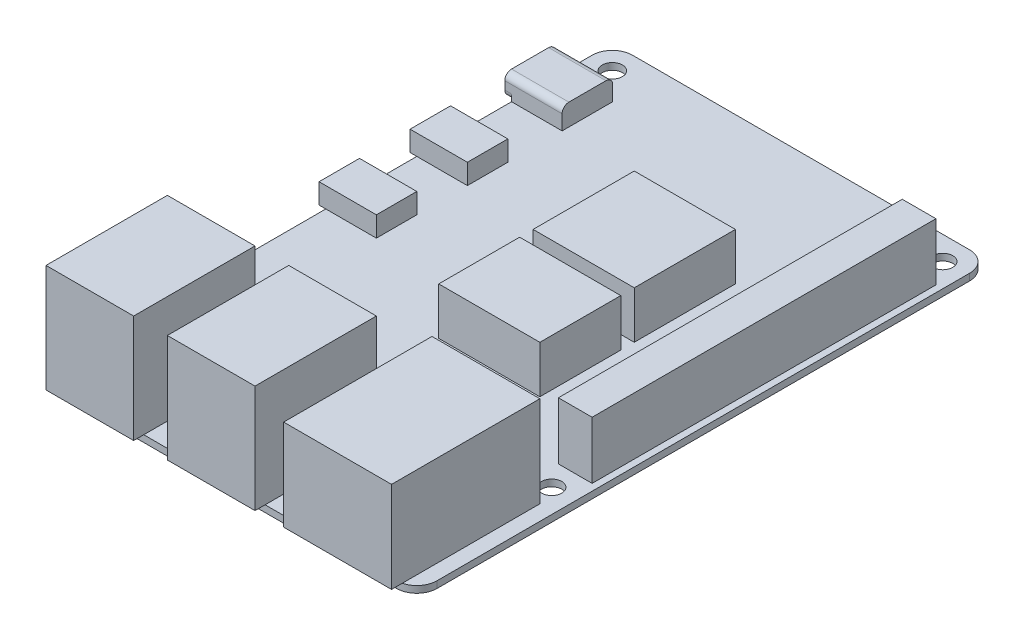
SolidWorks part; units mm, degrees
ref_plane "Plan de face" through (0, 0, 0) normal (0, 0, 1) x (1, 0, 0)
ref_plane "Plan de dessus" through (0, 0, 0) normal (0, 1, 0) x (1, 0, 0)
ref_plane "Plan de droite" through (0, 0, 0) normal (1, 0, 0) x (0, 0, -1)
sketch "Esquisse1" plane through (0, 0, 0) normal (0, 1, 0) x (1, 0, 0)
  line L0 (-24.5, 42.5) -> (-24.5, 39) construction
  line L1 (-25, -42.5) -> (25, -42.5)
  line L2 (-28, -39.5) -> (-28, 39.5)
  line L3 (-25, 42.5) -> (25, 42.5)
  line L4 (28, -39.5) -> (28, 39.5)
  line L5 (-28, -42.5) -> (28, 42.5) construction
  line L6 (-28, 42.5) -> (28, -42.5) construction
  line L7 (-24.5, 39) -> (-28, 39) construction
  line L8 (24.5, 42.5) -> (24.5, 39) construction
  line L9 (24.5, 39) -> (28, 39) construction
  line L10 (-24.5, 39) -> (-24.5, -19) construction
  line L11 (-24.5, -19) -> (24.5, -19) construction
  arc A0 (-25, -42.5) -> (-28, -39.5) centre (-25, -39.5) cw
  arc A1 (25, -42.5) -> (28, -39.5) centre (25, -39.5) ccw
  arc A2 (25, 42.5) -> (28, 39.5) centre (25, 39.5) cw
  arc A3 (-28, 39.5) -> (-25, 42.5) centre (-25, 39.5) cw
  circle A4 centre (-24.5, 39) radius 1.5
  circle A5 centre (24.5, 39) radius 1.5
  circle A6 centre (-24.5, -19) radius 1.5
  circle A7 centre (24.5, -19) radius 1.5
  point P0 (0, 0)
  dimension "D3" = 3
  dimension "D1" = 56
  dimension "D2" = 85
extrude "Boss.-Extru.1" add sketch "Esquisse1" along normal blind 1
sketch "Esquisse2" plane through (0, 1, 0) normal (0, 1, 0) x (1, 0, 0)
  line L0 (-28, -39.5) -> (-28, -75.4952) construction
  line L1 (-28, -75.4952) -> (-19, -75.4952) construction
  line L2 (-19, -75.4952) -> (-1, -75.4952) construction
  line L3 (-19, -75.4952) -> (-19, -42.5) construction
  line L4 (-25, -42.5) -> (25, -42.5) construction
  line L5 (-19, -42.5) -> (-19, -35) construction
  line L6 (-1, -75.4952) -> (-1, -42.5) construction
  line L7 (-12.5, -26) -> (-25.5, -26)
  line L8 (-12.5, -26) -> (-12.5, -44)
  line L9 (-12.5, -44) -> (-25.5, -44)
  line L10 (-25.5, -26) -> (-25.5, -44)
  line L11 (-12.5, -26) -> (-25.5, -44) construction
  line L12 (-12.5, -44) -> (-25.5, -26) construction
  line L13 (-1, -42.5) -> (-1, -35) construction
  line L15 (5.5, -26) -> (-7.5, -26)
  line L16 (5.5, -26) -> (5.5, -44)
  line L17 (5.5, -44) -> (-7.5, -44)
  line L18 (-7.5, -26) -> (-7.5, -44)
  line L19 (5.5, -26) -> (-7.5, -44) construction
  line L20 (5.5, -44) -> (-7.5, -26) construction
  dimension "D1" = 13
  dimension "D2" = 9
  dimension "D3" = 18
  dimension "D4" = 18
  dimension "D5" = 13
  dimension "D6" = 18
extrude "Boss.-Extru.2" add sketch "Esquisse2" along normal blind 16
sketch "Esquisse3" plane through (0, 1, 0) normal (0, 1, 0) x (1, 0, 0)
  line L0 (17.75, -42.5) -> (17.75, -33) construction
  line L1 (5.5, -42.5) -> (25, -42.5) construction
  line L2 (28, -39.5) -> (28, 39.5) construction
  line L4 (25.75, -22) -> (9.75, -22)
  line L5 (25.75, -22) -> (25.75, -44)
  line L6 (25.75, -44) -> (9.75, -44)
  line L7 (9.75, -22) -> (9.75, -44)
  line L8 (25.75, -22) -> (9.75, -44) construction
  line L9 (25.75, -44) -> (9.75, -22) construction
  dimension "D1" = 10.25
  dimension "D2" = 9.5
  dimension "D3" = 16
  dimension "D4" = 22
extrude "Boss.-Extru.3" add sketch "Esquisse3" along normal blind 13.5
sketch "Esquisse4" plane through (0, 1, 0) normal (0, 1, 0) x (1, 0, 0)
  line L0 (-28, 13.25) -> (4.5, 13.25) construction
  line L1 (-28, 39.5) -> (-28, -39.5) construction
  line L2 (25, 42.5) -> (-25, 42.5) construction
  line L3 (4.5, 13.25) -> (4.5, -2.25) construction
  line L4 (12, 20.75) -> (-3, 20.75)
  line L5 (12, 20.75) -> (12, 5.75)
  line L6 (12, 5.75) -> (-3, 5.75)
  line L7 (-3, 20.75) -> (-3, 5.75)
  line L8 (12, 20.75) -> (-3, 5.75) construction
  line L9 (12, 5.75) -> (-3, 20.75) construction
  line L11 (12, 3.75) -> (-3, 3.75)
  line L12 (12, 3.75) -> (12, -8.25)
  line L13 (12, -8.25) -> (-3, -8.25)
  line L14 (-3, 3.75) -> (-3, -8.25)
  line L15 (12, 3.75) -> (-3, -8.25) construction
  line L16 (12, -8.25) -> (-3, 3.75) construction
  dimension "D1" = 29.25
  dimension "D2" = 32.5
  dimension "D3" = 15
  dimension "D4" = 15
  dimension "D5" = 12
  dimension "D6" = 15
  dimension "D7" = 2
extrude "Boss.-Extru.4" add sketch "Esquisse4" along normal blind 7
sketch "Esquisse5" plane through (0, 1, 0) normal (0, 1, 0) x (1, 0, 0)
  line L0 (-24.75, 42.5) -> (-24.75, 31.3) construction
  line L1 (25, 42.5) -> (-25, 42.5) construction
  line L2 (-24.75, 31.3) -> (-28, 31.3) construction
  line L3 (-28, 39.5) -> (-28, -39.5) construction
  line L4 (-28, 31.3) -> (-29, 31.3) construction
  line L6 (-20.5, 35.05) -> (-29, 35.05)
  line L7 (-20.5, 35.05) -> (-20.5, 27.55)
  line L8 (-20.5, 27.55) -> (-29, 27.55)
  line L9 (-29, 35.05) -> (-29, 27.55)
  line L10 (-20.5, 35.05) -> (-29, 27.55) construction
  line L11 (-20.5, 27.55) -> (-29, 35.05) construction
  dimension "D1" = 1
  dimension "D2" = 3.25
  dimension "D3" = 8.5
  dimension "D4" = 7.5
extrude "Boss.-Extru.5" add sketch "Esquisse5" along normal blind 3.2
fillet "Congé3" radius 1 2 edges at (-24.75, 4.2, -35.05) (-24.75, 4.2, -27.55)
fillet "Congé4" radius 1 2 edges at (-28.5, 1, -27.55) (-28.5, 1, -35.05)
sketch "Esquisse6" plane through (0, 1, 0) normal (0, 1, 0) x (1, 0, 0)
  line L0 (-28, 16.5) -> (-24.75, 16.5) construction
  line L1 (-28, 27.55) -> (-28, -39.5) construction
  line L2 (-24.75, 16.5) -> (-24.75, 3) construction
  line L3 (25, 42.5) -> (-25, 42.5) construction
  line L5 (-29, 19.5) -> (-20.5, 19.5)
  line L6 (-29, 19.5) -> (-29, 13.5)
  line L7 (-29, 13.5) -> (-20.5, 13.5)
  line L8 (-20.5, 19.5) -> (-20.5, 13.5)
  line L9 (-29, 19.5) -> (-20.5, 13.5) construction
  line L10 (-29, 13.5) -> (-20.5, 19.5) construction
  line L11 (-29, 6) -> (-20.5, 6)
  line L12 (-29, 6) -> (-29, 0)
  line L13 (-29, 0) -> (-20.5, 0)
  line L14 (-20.5, 6) -> (-20.5, 0)
  line L15 (-29, 6) -> (-20.5, 0) construction
  line L16 (-29, 0) -> (-20.5, 6) construction
  dimension "D1" = 26
  dimension "D2" = 13.5
  dimension "D3" = 3.25
  dimension "D4" = 8.5
  dimension "D5" = 8.5
  dimension "D6" = 6
  dimension "D7" = 6
extrude "Boss.-Extru.6" add sketch "Esquisse6" along normal blind 3
sketch "Esquisse7" plane through (0, 1, 0) normal (0, 1, 0) x (1, 0, 0)
  line L0 (24.5, 42.5) -> (24.5, 10) construction
  line L1 (25, 42.5) -> (-25, 42.5) construction
  line L2 (24.5, 10) -> (28, 10) construction
  line L3 (28, -39.5) -> (28, 39.5) construction
  line L5 (22, 35.5) -> (27, 35.5)
  line L6 (22, 35.5) -> (22, -15.5)
  line L7 (22, -15.5) -> (27, -15.5)
  line L8 (27, 35.5) -> (27, -15.5)
  line L9 (22, 35.5) -> (27, -15.5) construction
  line L10 (22, -15.5) -> (27, 35.5) construction
  dimension "D1" = 3.5
  dimension "D2" = 32.5
  dimension "D3" = 51
  dimension "D4" = 5
extrude "Boss.-Extru.7" add sketch "Esquisse7" along normal blind 8.5
